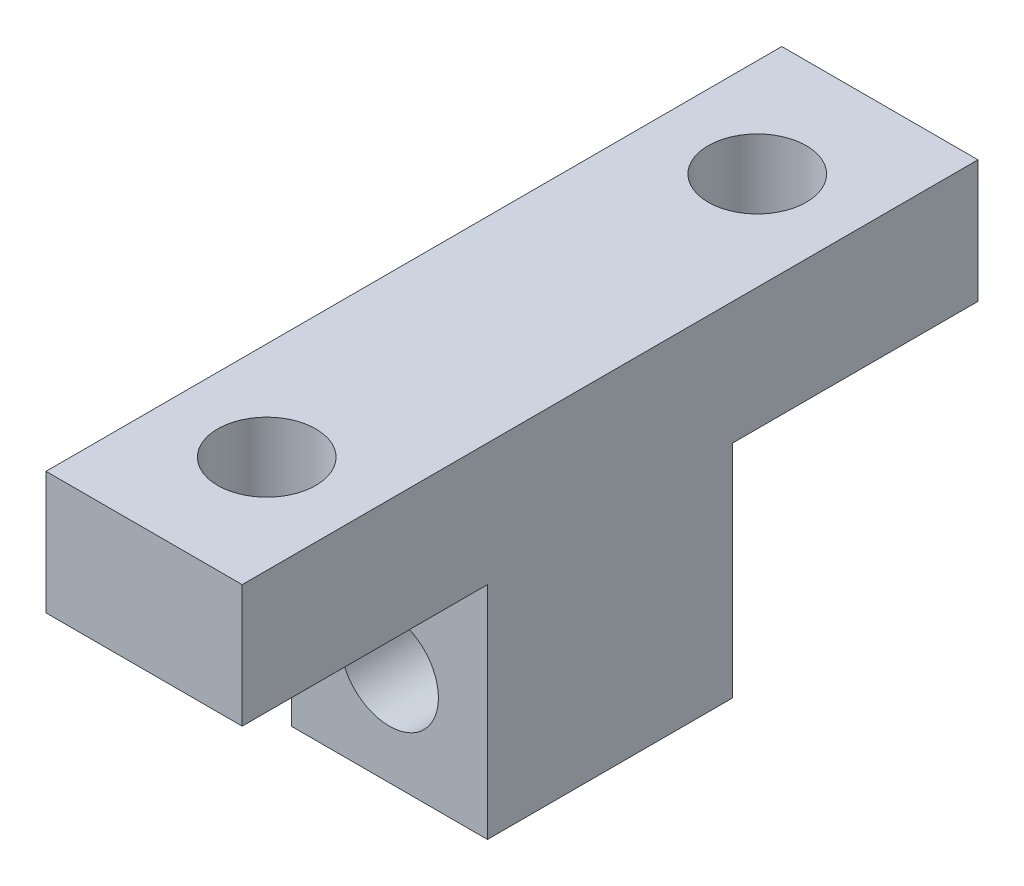
SolidWorks part; units mm, degrees
material "1060 合金"
ref_plane "前视基准面" through (0, 0, 0) normal (0, 0, 1) x (1, 0, 0)
ref_plane "上视基准面" through (0, 0, 0) normal (0, 1, 0) x (1, 0, 0)
ref_plane "右视基准面" through (0, 0, 0) normal (1, 0, 0) x (0, 0, -1)
sketch "草图1" plane through (0, 0, 0) normal (1, 0, 0) x (0, 0, -1)
  line L0 (-59.266, 0) -> (57.3175, 0) construction
  line L1 (-15, 0) -> (-15, -5)
  line L2 (-15, -5) -> (-5, -5)
  line L3 (-5, -5) -> (-5, -14)
  line L4 (-5, -14) -> (5, -14)
  line L5 (-15, 0) -> (0, 0)
  line L8 (0, 25.5575) -> (0, -39.3204) construction
  line L11 (15, 0) -> (0, 0)
  line L12 (5, -5) -> (5, -14)
  line L13 (15, -5) -> (5, -5)
  line L14 (15, 0) -> (15, -5)
  point P18 (0, -14)
  dimension "D1" = 5
  dimension "D4" = 14
  dimension "D5" = 15
  dimension "D6" = 10
  dimension "D7" = 5
extrude "凸台-拉伸1" add sketch "草图1" along normal mid plane 8
sketch "草图2" plane through (0, 0, 0) normal (0, 1, 0) x (1, 0, 0)
  line L0 (4, 0) -> (-4, 0) construction
  line L3 (4, 15) -> (-4, 15) construction
  line L4 (4, 15) -> (4, -15) construction
  line L5 (-4, 15) -> (-4, -15) construction
  circle A0 centre (0, 10) radius 2
  circle A1 centre (0, -10) radius 2
  dimension "D1" = 4
  dimension "D2" = 5
extrude "切除-拉伸1" cut sketch "草图2" against normal up to next
sketch "草图3" plane through (0, 0, 0) normal (0, 0, 1) x (1, 0, 0)
  circle A0 centre (0, -10) radius 2
  dimension "D1" = 4
  dimension "D2" = 10
extrude "切除-拉伸2" cut sketch "草图3" against normal through all both and the other way through all
